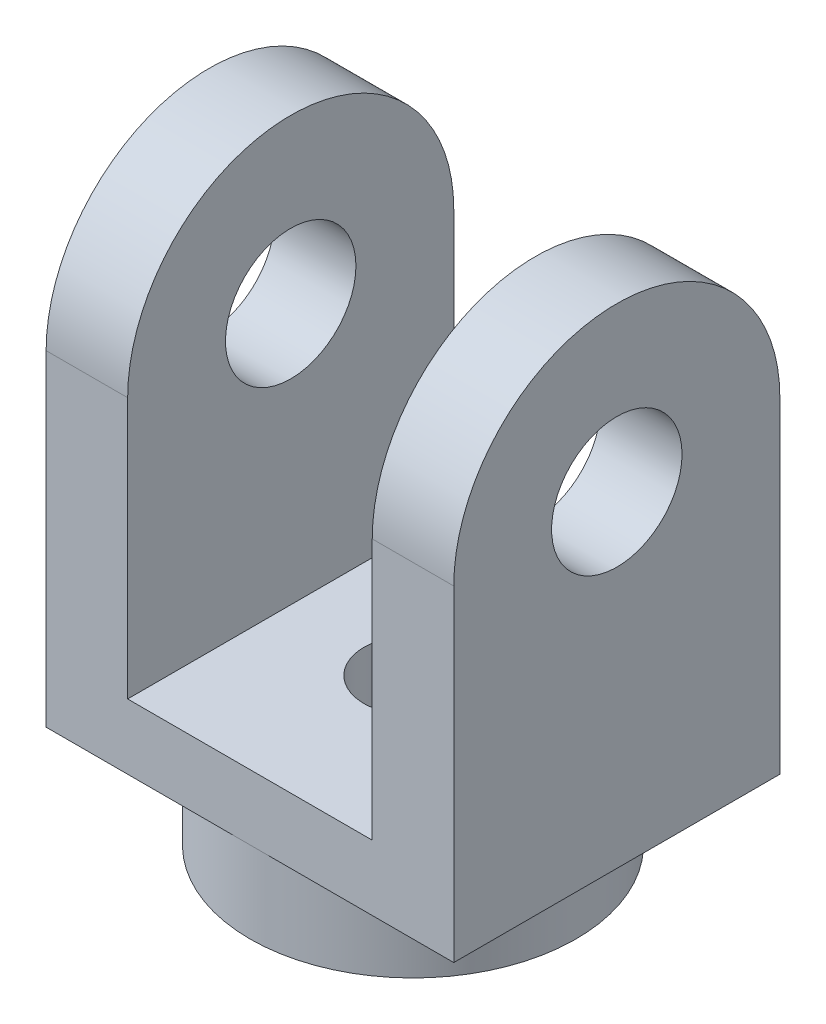
SolidWorks part; units mm, degrees
ref_plane "Front" through (0, 0, 0) normal (0, 0, 1) x (1, 0, 0)
ref_plane "Top" through (0, 0, 0) normal (0, 1, 0) x (1, 0, 0)
ref_plane "Right" through (0, 0, 0) normal (1, 0, 0) x (0, 0, -1)
sketch "Sketch1" plane through (0, 0, 0) normal (0, 1, 0) x (1, 0, 0)
  circle A0 centre (0, 0) radius 37.5
  circle A1 centre (0, 0) radius 50
  dimension "D1" = 75
  dimension "D2" = 100
extrude "Boss-Extrude1" add sketch "Sketch1" against normal blind 25 contours A1 A0
sketch "Sketch2" plane through (0, 0, 0) normal (1, 0, 0) x (0, 0, -1)
  line L0 (-50, 0) -> (50, 0)
  line L1 (50, 0) -> (50, 100)
  line L2 (-50, 100) -> (-50, 0)
  line L3 (50, 0) -> (-50, 0) construction
  line L4 (-50, 0) -> (-50, -25) construction
  arc A0 (50, 100) -> (-50, 100) centre (0, 100) ccw
  dimension "D1" = 100
  dimension "D2" = 100
extrude "Boss-Extrude2" add sketch "Sketch2" along normal mid plane 125 contours A0 L2 L0 L1
sketch "Sketch3" plane through (0, 0, 50) normal (0, 0, 1) x (1, 0, 0)
  line L0 (-62.5, 150) -> (62.5, 150) construction
  line L2 (-37.5, 150) -> (37.5, 150)
  line L3 (-37.5, 150) -> (-37.5, 20)
  line L4 (-37.5, 20) -> (37.5, 20)
  line L5 (37.5, 150) -> (37.5, 20)
  point P8 (0, 150)
  dimension "D1" = 75
  dimension "D2" = 130
extrude "Cut-Extrude1" cut sketch "Sketch3" against normal through all both and the other way through all
sketch "Sketch4" plane through (0, 20, 0) normal (0, 1, 0) x (1, 0, 0)
  circle A0 centre (0, 0) radius 15
  dimension "D1" = 30
extrude "Cut-Extrude2" cut sketch "Sketch4" against normal through all
sketch "Sketch5" plane through (62.5, 0, 0) normal (1, 0, 0) x (0, 0, -1)
  circle A0 centre (0, 100) radius 20
  dimension "D1" = 40
extrude "Cut-Extrude3" cut sketch "Sketch5" against normal through all
